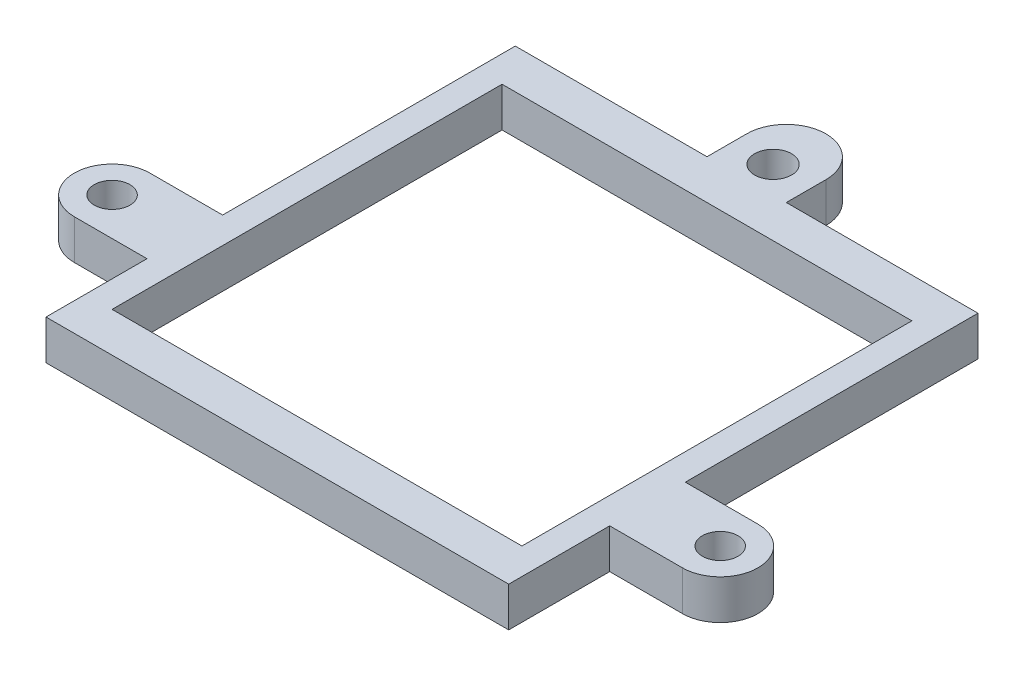
SolidWorks part; units mm, degrees
ref_plane "Front Plane" through (0, 0, 0) normal (0, 0, 1) x (1, 0, 0)
ref_plane "Top Plane" through (0, 0, 0) normal (0, 1, 0) x (1, 0, 0)
ref_plane "Right Plane" through (0, 0, 0) normal (1, 0, 0) x (0, 0, -1)
sketch "Sketch1" plane through (0, 0, 0) normal (0, 1, 0) x (1, 0, 0)
  line L0 (0, -44.7868) -> (0, 44.7868) construction
  line L1 (-17.5, 17.75) -> (17.5, 17.75)
  line L2 (-17.5, 17.75) -> (-17.5, -17.75)
  line L3 (-17.5, -17.75) -> (17.5, -17.75)
  line L4 (17.5, 17.75) -> (17.5, -17.75)
  line L5 (-44.2539, 0) -> (44.2539, 0) construction
  line L6 (-3, 17.75) -> (-3, 20.75)
  line L7 (-15.5, 14.75) -> (15.5, 14.75)
  line L8 (-15.5, 14.75) -> (-15.5, -14.75)
  line L9 (-15.5, -14.75) -> (15.5, -14.75)
  line L10 (15.5, 14.75) -> (15.5, -14.75)
  line L11 (3, 17.75) -> (3, 20.75)
  line L12 (17.5, -10.1101) -> (23, -10.1101)
  line L13 (17.5, -4.3899) -> (23, -4.3899)
  line L14 (-17.5, -10.1101) -> (-23, -10.1101)
  line L15 (-17.5, -4.3899) -> (-23, -4.3899)
  arc A0 (-3, 20.75) -> (3, 20.75) centre (0, 20.75) cw
  circle A2 centre (0, 19.75) radius 1.4
  arc A3 (23, -4.3899) -> (23, -10.1101) centre (23, -7.25) cw
  arc A4 (-23, -10.1101) -> (-23, -4.3899) centre (-23, -7.25) cw
  circle A5 centre (-23, -7.25) radius 1.35
  circle A6 centre (23, -7.25) radius 1.35
  dimension "D9" = 3
  dimension "D12" = 2.8
  dimension "D14" = 46
  dimension "D15" = 2.7
  dimension "D16" = 2.7
  dimension "D1" = 35
  dimension "D2" = 17.5
  dimension "D3" = 35.5
  dimension "D4" = 17.75
  dimension "D5" = 2
  dimension "D6" = 2
  dimension "D7" = 3
  dimension "D8" = 3
  dimension "D10" = 3
  dimension "D11" = 17.5
  dimension "D13" = 5
  dimension "D17" = 27
  dimension "D18" = 22.1399
extrude "Boss-Extrude3" add sketch "Sketch1" along normal blind 3 contours A4 L14 L2 L15 A5 | L4 L1 L2 L3 L7 L10 L9 L8 | A3 L13 L4 L12 A6 | A0 L6 L1 L11 A2
